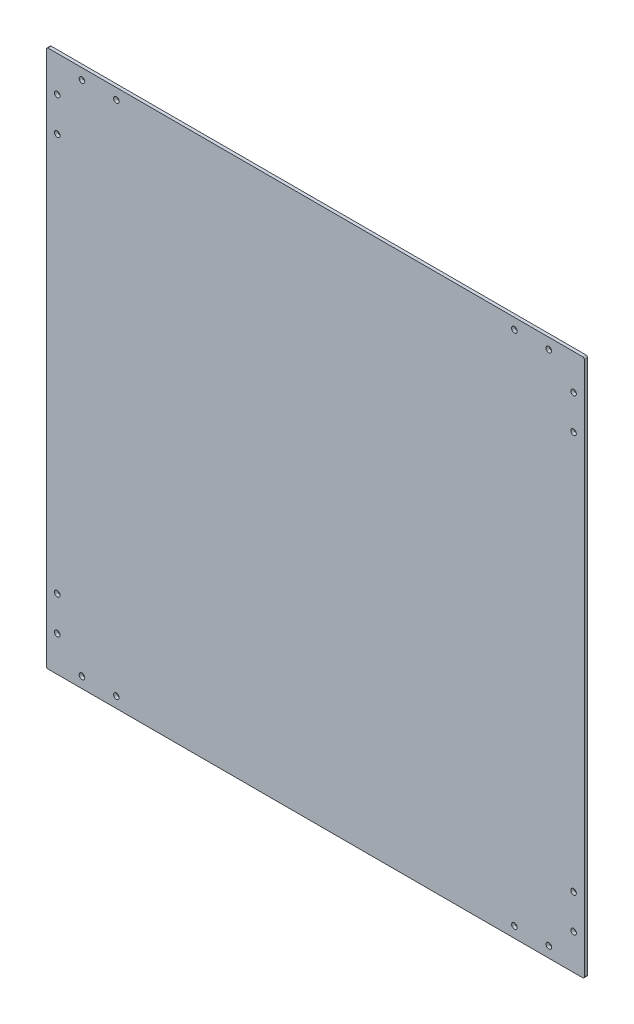
SolidWorks part; units mm, degrees
material "ABS PC"
ref_plane "Front Plane" through (0, 0, 0) normal (0, 0, 1) x (1, 0, 0)
ref_plane "Top Plane" through (0, 0, 0) normal (0, 1, 0) x (1, 0, 0)
ref_plane "Right Plane" through (0, 0, 0) normal (1, 0, 0) x (0, 0, -1)
sketch "Sketch1" plane through (0, 0, 0) normal (0, 0, 1) x (1, 0, 0)
  line L0 (-207.5662, 10) -> (-171, 10) construction
  line L1 (-250, 10) -> (250, 10)
  line L2 (-250, 10) -> (-250, -490)
  line L3 (-250, -490) -> (250, -490)
  line L4 (250, 10) -> (250, -490)
  line L5 (-250, -29.4338) -> (-250, 7) construction
  line L6 (250, -32.4338) -> (250, -69) construction
  line L7 (207.5662, -490) -> (171, -490) construction
  line L8 (0, 10) -> (0, -240) construction
  line L9 (0, -240) -> (-250, -240) construction
  circle A0 centre (-185, 0) radius 2.6 construction
  circle A1 centre (-217, 0) radius 2.6 construction
  circle A2 centre (-240, -23) radius 2.6 construction
  circle A3 centre (-240, -55) radius 2.6 construction
  circle A4 centre (-185, 0) radius 2.6
  circle A5 centre (-217, 0) radius 2.6
  circle A6 centre (-240, -23) radius 2.6
  circle A7 centre (-240, -55) radius 2.6
  circle A8 centre (-240, -425) radius 2.6
  circle A9 centre (-240, -457) radius 2.6
  circle A10 centre (-217, -480) radius 2.6
  circle A11 centre (-185, -480) radius 2.6
  circle A12 centre (185, -480) radius 2.6
  circle A13 centre (217, -480) radius 2.6
  circle A14 centre (240, -457) radius 2.6
  circle A15 centre (240, -425) radius 2.6
  circle A16 centre (240, -55) radius 2.6
  circle A17 centre (240, -23) radius 2.6
  circle A18 centre (217, 0) radius 2.6
  circle A19 centre (185, 0) radius 2.6
extrude "Boss-Extrude1" add sketch "Sketch1" along normal blind 3
fillet "Fillet1" radius 1.5 4 edges at (250, -490, 1.5) (-250, -490, 1.5) (-250, 10, 1.5) (250, 10, 1.5)
